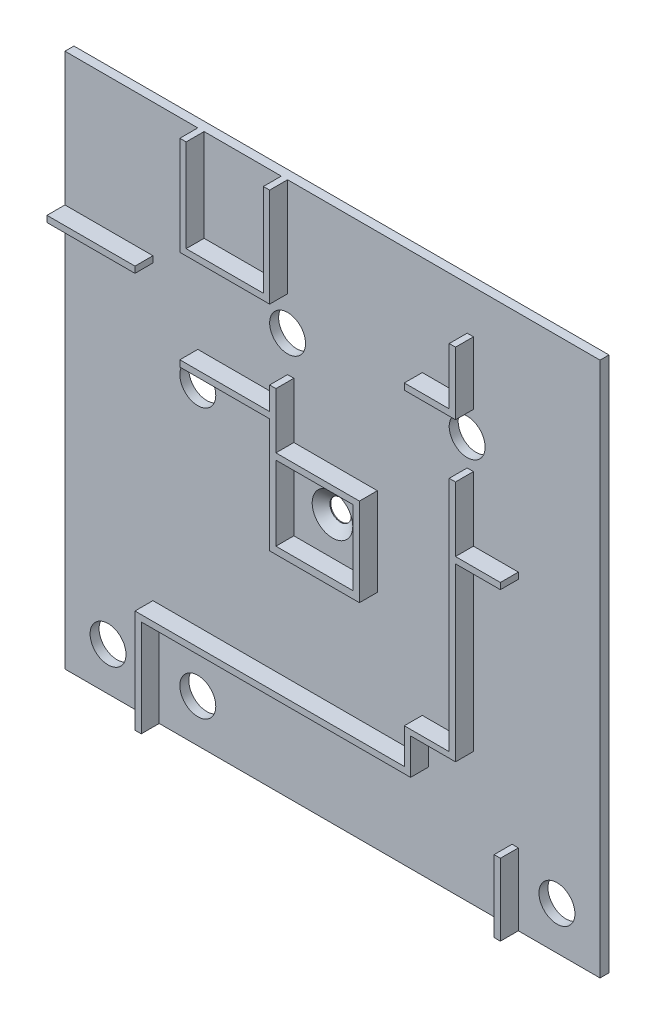
SolidWorks part; units mm, degrees
ref_plane "Front Plane" through (0, 0, 0) normal (0, 0, 1) x (1, 0, 0)
ref_plane "Top Plane" through (0, 0, 0) normal (0, 1, 0) x (1, 0, 0)
ref_plane "Right Plane" through (0, 0, 0) normal (1, 0, 0) x (0, 0, -1)
sketch "Sketch3" plane through (0, 0, 0) normal (0, 0, 1) x (1, 0, 0)
  line L1 (-149, 149) -> (149, 149)
  line L2 (-149, 149) -> (-149, -149)
  line L3 (-149, -149) -> (149, -149)
  line L4 (149, 149) -> (149, -149)
  line L5 (-149, 149) -> (149, -149) construction
  line L6 (-149, -149) -> (149, 149) construction
  point P0 (0, 0)
  dimension "D1" = 298
  dimension "D2" = 298
extrude "Boss-Extrude2" add sketch "Sketch3" along normal blind 5
sketch "Sketch4" plane through (0, 0, 5) normal (0, 0, 1) x (1, 0, 0)
  line L0 (-149, 149) -> (-125, 149)
  line L1 (149, 149) -> (-149, 149) construction
  line L2 (-125, 149) -> (-75, 149)
  line L3 (-75, 149) -> (-25, 149)
  line L4 (-25, 149) -> (25, 149)
  line L5 (25, 149) -> (75, 149)
  line L6 (75, 149) -> (125, 149)
  line L7 (125, 149) -> (149, 149)
  line L15 (-149, 149) -> (-149, 125)
  line L16 (-149, 149) -> (-149, -149) construction
  line L17 (-149, 125) -> (-149, 75)
  line L18 (-149, 75) -> (-149, 25)
  line L19 (-149, 25) -> (-149, -25)
  line L20 (-149, -25) -> (-149, -75)
  line L21 (-149, -75) -> (-149, -125)
  line L22 (-149, -125) -> (-149, -149)
  circle A5 centre (-125, -125) radius 10
  circle A8 centre (-75, 25) radius 10
  circle A11 centre (-75, -125) radius 10
  circle A13 centre (-25, 75) radius 10
  circle A25 centre (75, 75) radius 10
  circle A30 centre (125, -125) radius 10
  dimension "D2" = 20
  dimension "D14" = 20
  dimension "D24" = 20
extrude "Cut-Extrude5" cut sketch "Sketch4" against normal blind 56 contours A8 | A13 | A25 | A11 | A5 | A30
sketch "Sketch5" plane through (0, 0, 5) normal (0, 0, 1) x (1, 0, 0)
  line L1 (149, 149) -> (-149, 149) construction
  line L9 (-149, 149) -> (-149, -149) construction
  line L17 (-149, -149) -> (149, -149) construction
  line L23 (-25, 24.0198) -> (-21.5, 24.0198)
  line L24 (-25, 24.0198) -> (-25, -25)
  line L25 (-25, -25) -> (-21.5, -25)
  line L26 (-21.5, 24.0198) -> (-21.5, -25)
  line L27 (25, -25) -> (21.5, -25)
  line L28 (25, -25) -> (25, 24.0198)
  line L29 (25, 24.0198) -> (21.5, 24.0198)
  line L30 (21.5, -25) -> (21.5, 24.0198)
  line L31 (-21.5, 20.5198) -> (21.5, 20.5198)
  line L32 (-21.5, 20.5198) -> (-21.5, 24.0198)
  line L33 (-21.5, 24.0198) -> (21.5, 24.0198)
  line L34 (21.5, 20.5198) -> (21.5, 24.0198)
  line L35 (21.5, -25) -> (-21.5, -25)
  line L36 (21.5, -25) -> (21.5, -20.9913)
  line L37 (21.5, -20.9913) -> (-21.5, -20.9913)
  line L38 (-21.5, -25) -> (-21.5, -20.9913)
  line L42 (-25, 55.0198) -> (-25, 42.1706)
  line L43 (-75, 149) -> (-71.5, 149)
  line L44 (-75, 149) -> (-75, 94)
  line L45 (-75, 94) -> (-71.5, 94)
  line L46 (-71.5, 149) -> (-71.5, 94)
  line L47 (-25, 149) -> (-28.5, 149)
  line L48 (-25, 149) -> (-25, 94)
  line L49 (-25, 94) -> (-28.5, 94)
  line L50 (-28.5, 149) -> (-28.5, 94)
  line L51 (-28.5, 94) -> (-71.5, 94)
  line L52 (-28.5, 94) -> (-28.5, 97.5)
  line L53 (-28.5, 97.5) -> (-71.5, 97.5)
  line L54 (-71.5, 94) -> (-71.5, 97.5)
  line L55 (-25, 24.0198) -> (-21.5, 24.0198)
  line L56 (-25, 24.0198) -> (-25, 55.0198)
  line L57 (-25, 55.0198) -> (-21.5, 55.0198)
  line L58 (-21.5, 24.0198) -> (-21.5, 55.0198)
  line L59 (-25, 38.6706) -> (-75, 38.6706)
  line L60 (-25, 38.6706) -> (-25, 42.1706)
  line L61 (-25, 42.1706) -> (-75, 42.1706)
  line L62 (-75, 38.6706) -> (-75, 42.1706)
  line L64 (-149, 74.8451) -> (-100, 74.8451)
  line L65 (-149, 74.8451) -> (-149, 71.3451)
  line L66 (-149, 71.3451) -> (-100, 71.3451)
  line L67 (-100, 74.8451) -> (-100, 71.3451)
  line L70 (-100, -149) -> (-96.5, -149)
  line L71 (-100, -149) -> (-100, -91.5)
  line L72 (-100, -91.5) -> (-96.5, -91.5)
  line L73 (-96.5, -149) -> (-96.5, -91.5)
  line L74 (-96.5, -91.5) -> (53.5, -91.5)
  line L75 (-96.5, -91.5) -> (-96.5, -95)
  line L76 (-96.5, -95) -> (53.5, -95)
  line L77 (53.5, -91.5) -> (53.5, -95)
  line L79 (100, -149) -> (103.5, -149)
  line L80 (100, -149) -> (100, -109)
  line L81 (100, -109) -> (103.5, -109)
  line L82 (103.5, -149) -> (103.5, -109)
  line L86 (53.5, -91.5) -> (50, -91.5)
  line L87 (53.5, -91.5) -> (53.5, -75)
  line L88 (53.5, -75) -> (50, -75)
  line L89 (50, -91.5) -> (50, -75)
  line L90 (50, -75) -> (75, -75)
  line L91 (50, -75) -> (50, -71.8422)
  line L92 (50, -71.8422) -> (75, -71.8422)
  line L93 (75, -75) -> (75, -71.8422)
  line L98 (75, -75) -> (78.5, -75)
  line L99 (75, -75) -> (75, 60)
  line L100 (75, 60) -> (78.5, 60)
  line L101 (78.5, -75) -> (78.5, 60)
  line L102 (75, 125) -> (78.5, 125)
  line L103 (75, 125) -> (75, 90)
  line L104 (75, 90) -> (78.5, 90)
  line L105 (78.5, 125) -> (78.5, 90)
  line L106 (75, 90) -> (50, 90)
  line L107 (75, 90) -> (75, 93.5)
  line L108 (75, 93.5) -> (50, 93.5)
  line L109 (50, 90) -> (50, 93.5)
  line L110 (78.5, 24.0198) -> (103.5, 24.0198)
  line L111 (78.5, 24.0198) -> (78.5, 20.5198)
  line L112 (78.5, 20.5198) -> (103.5, 20.5198)
  line L113 (103.5, 24.0198) -> (103.5, 20.5198)
  line M92 (149, 149) -> (-149, 149)
  line M93 (-149, 149) -> (-149, -149)
  line M94 (-149, -149) -> (149, -149)
  dimension "D1" = 3.5
  dimension "D2" = 3.5
  dimension "D3" = 43
  dimension "D14" = 31
  dimension "D15" = 3.5
  dimension "D16" = 49
  dimension "D17" = 3.5
  dimension "D18" = 57.5
  dimension "D19" = 3.5
  dimension "D20" = 3.5
  dimension "D21" = 150
  dimension "D23" = 3.5
  dimension "D25" = 3.5
  dimension "D26" = 25
  dimension "D27" = 3.5
  dimension "D28" = 135
  dimension "D29" = 35
  dimension "D30" = 3.5
  dimension "D31" = 25
  dimension "D32" = 3.5
  dimension "D33" = 25
  dimension "D34" = 3.5
extrude "Boss-Extrude6" add sketch "Sketch5" along normal blind 10 contours L46 L44 L45 M92 | L50 L53 L46 L51 | L50 L49 L48 M92 | L67 L64 L66 M93 | L23 L58 L57 L42 L56 | L26 L23 L24 L25 | L33 L26 L31 L30 | L30 L27 L28 L29 | L30 L37 L26 L35 | L98 L101 L100 L99 L93 | L113 L110 L101 L112 | L105 L102 L103 L104 | L109 L106 L103 L108 | L90 L93 L92 L91 L88 | L89 L74 L87 L88 | L77 L74 L73 L76 | L73 L72 L71 M94 | L82 L81 L80 M94 | L61 L62 L59 L60
hole_wizard "CSK for 7/16 Flat Head Machine Screw (100)1" positions "Sketch6" profile "Sketch7" countersink size "7/16" standard "ANSI Inch" end condition through all
sketch "Sketch6" plane through (0, 0, 5) normal (0, 0, 1) x (1, 0, 0)
  point P0 (0, 0)
sketch "Sketch7" plane through (0, 0, 5) normal (1, 0, 0) x (0, -1, 0)
  line L0 (0, 0) -> (0, 5)
  line L1 (0, 5) -> (5.9525, 5)
  line L2 (5.9525, 5) -> (5.9525, 4.4896)
  line L3 (5.9525, 4.4896) -> (11.303, 0)
  line L5 (11.303, 0) -> (0, 0)
  line L6 (-5.9525, 4.4896) -> (-11.303, 0) construction
  line L11 (0, -6.35) -> (0, 107.95) construction
  dimension "Thru Hole Dia." = 11.905
  dimension "Thru Hole Depth" = 5
  dimension "Near C'Sink Dia." = 22.606
  dimension "Near C'Sink Angle" = 100
split "Split1" bodies to split 116 resulting bodies 117
